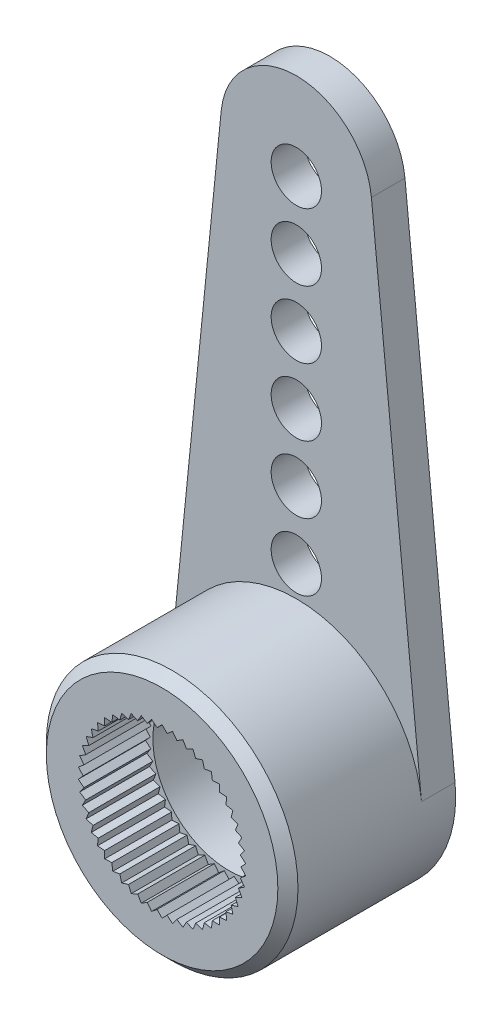
SolidWorks part; units mm, degrees
material "ABS PC"
ref_plane "Front" through (0, 0, 0) normal (0, 0, 1) x (1, 0, 0)
ref_plane "Top" through (0, 0, 0) normal (0, 1, 0) x (1, 0, 0)
ref_plane "Right" through (0, 0, 0) normal (1, 0, 0) x (0, 0, -1)
sketch "Sketch1" plane through (0, 0, 0) normal (0, 0, 1) x (1, 0, 0)
  line L0 (-3.7312, 0.375) -> (-2.2387, 15.225)
  line L1 (2.2387, 15.225) -> (3.7312, 0.375)
  arc A0 (-3.7312, 0.375) -> (3.7312, 0.375) centre (0, 0) ccw
  arc A1 (2.2387, 15.225) -> (-2.2387, 15.225) centre (0, 15) ccw
  dimension "D1" = 4.5
  dimension "D2" = 7.5
  dimension "D3" = 15
extrude "Boss-Extrude1" add sketch "Sketch1" along normal blind 1
sketch "Sketch2" plane through (0, 0, 1) normal (0, 0, 1) x (1, 0, 0)
  arc A0 (-3.7312, 0.375) -> (3.7312, 0.375) centre (0, 0) ccw construction
  arc A1 (-3.7312, 0.375) -> (3.7312, 0.375) centre (0, 0) ccw construction
  circle A2 centre (0, 0) radius 3.75
  circle A3 centre (0, 0) radius 2.275
  dimension "D1" = 4.55
extrude "Boss-Extrude2" add sketch "Sketch2" along normal blind 4
sketch "Sketch7" plane through (0, 0, 5) normal (0, 0, 1) x (1, 0, 0)
  line L0 (0, 0) -> (0, 2.5) construction
  line L1 (0, 0) -> (0.157, 2.4951) construction
  line L2 (0, 0) -> (-0.157, 2.4951) construction
  line L3 (0, 2.5) -> (-0.1476, 2.3454)
  line L4 (0, 2.5) -> (0.1476, 2.3454)
  line L5 (-0.1476, 2.3454) -> (-0.1428, 2.2705)
  line L6 (0.1476, 2.3454) -> (0.1428, 2.2705)
  circle A0 centre (0, 0) radius 2.5 construction
  circle A1 centre (0, 0) radius 2.35 construction
  circle A2 centre (0, 0) radius 2.275 construction
  circle A3 centre (0, 0) radius 2.275
  circle M2 centre (0, 0) radius 2.275
  dimension "D1" = 5
  dimension "D2" = 4.7
  dimension "D3" = 3.6
sketch "Sketch3" plane through (0, 0, 0) normal (0, 0, -1) x (-1, 0, 0)
  circle A0 centre (0, 0) radius 2
  dimension "D1" = 4
extrude "Cut-Extrude1" cut sketch "Sketch3" against normal blind 0.8
sketch "Sketch4" plane through (0, 0, 0.8) normal (0, 0, -1) x (-1, 0, 0)
  circle A0 centre (0, 0) radius 0.75
  dimension "D1" = 1.5
extrude "Cut-Extrude2" cut sketch "Sketch4" against normal up to surface (0.2 mm away) up to face at (2.275, 0, 1)
sketch "Sketch5" plane through (0, 0, 0) normal (0, 0, -1) x (-1, 0, 0)
  circle A0 centre (0, 4.65) radius 0.75
  circle A1 centre (0, 6.65) radius 0.75
  circle A2 centre (0, 8.65) radius 0.75
  circle A3 centre (0, 10.65) radius 0.75
  circle A4 centre (0, 12.65) radius 0.75
  circle A5 centre (0, 14.65) radius 0.75
  dimension "D1" = 1.5
  dimension "D2" = 4.65
  dimension "D4" = 2
  dimension "D3" = 6
extrude "Cut-Extrude3" cut sketch "Sketch5" against normal up to surface (1 mm away) up to face at (0, 9.15, 1)
chamfer "Chamfer1" distance 0.3 angle 45 1 edges at (3.75, 0, 5)
extrude "Cut-Extrude4" cut sketch "Sketch7" against normal blind 2 contours L6 L4 L3 L5 M2
pattern_circular "CirPattern1" count 50 over 360 about axis through (0, 0, 0) along (0, 0, 1) of "Cut-Extrude4"
